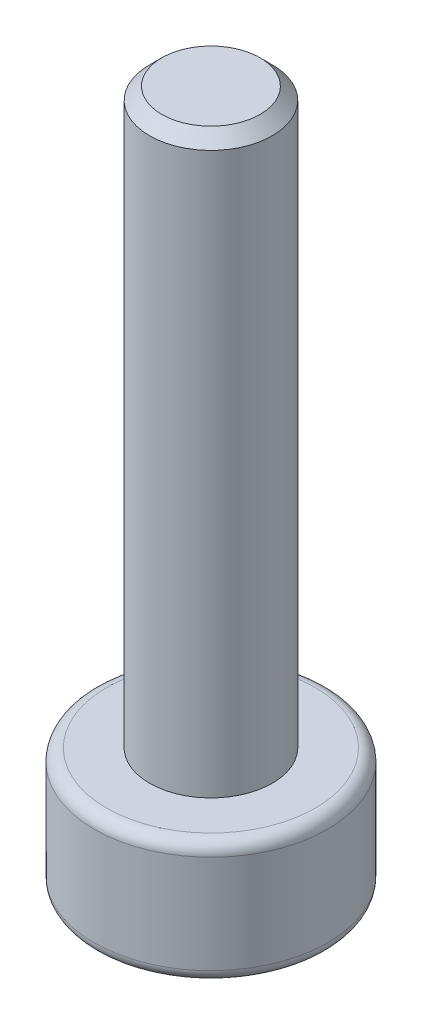
SolidWorks part; units mm, degrees
material "AISI 304"
ref_plane "前视基准面" through (0, 0, 0) normal (0, 0, 1) x (1, 0, 0)
ref_plane "上视基准面" through (0, 0, 0) normal (0, 1, 0) x (1, 0, 0)
ref_plane "右视基准面" through (0, 0, 0) normal (1, 0, 0) x (0, 0, -1)
sketch "草图1" plane through (0, 0, 0) normal (0, 1, 0) x (1, 0, 0)
  circle A0 centre (0, 0) radius 2.85
  dimension "D1" = 5.7
extrude "凸台-拉伸1" add sketch "草图1" along normal blind 3
sketch "草图2" plane through (0, 3, 0) normal (0, 1, 0) x (1, 0, 0)
  circle A0 centre (0, 0) radius 1.5
  dimension "D1" = 3
extrude "凸台-拉伸2" add sketch "草图2" along normal blind 14
sketch "草图3" plane through (0, 0, 0) normal (0, -1, 0) x (1, 0, 0)
  circle A0 centre (0, 0) radius 1.29
  dimension "D1" = 2.58
extrude "切除-拉伸1" cut sketch "草图3" against normal blind 1.3
fillet "圆角1" radius 0.3 2 edges at (0, 3, 2.85) (0, 0, 2.85)
chamfer "倒角1" distance 0.3 angle 45 1 edges at (0, 17, 1.5)
chamfer "倒角2" distance 0.15 angle 45 1 edges at (0, 0, -1.29)
